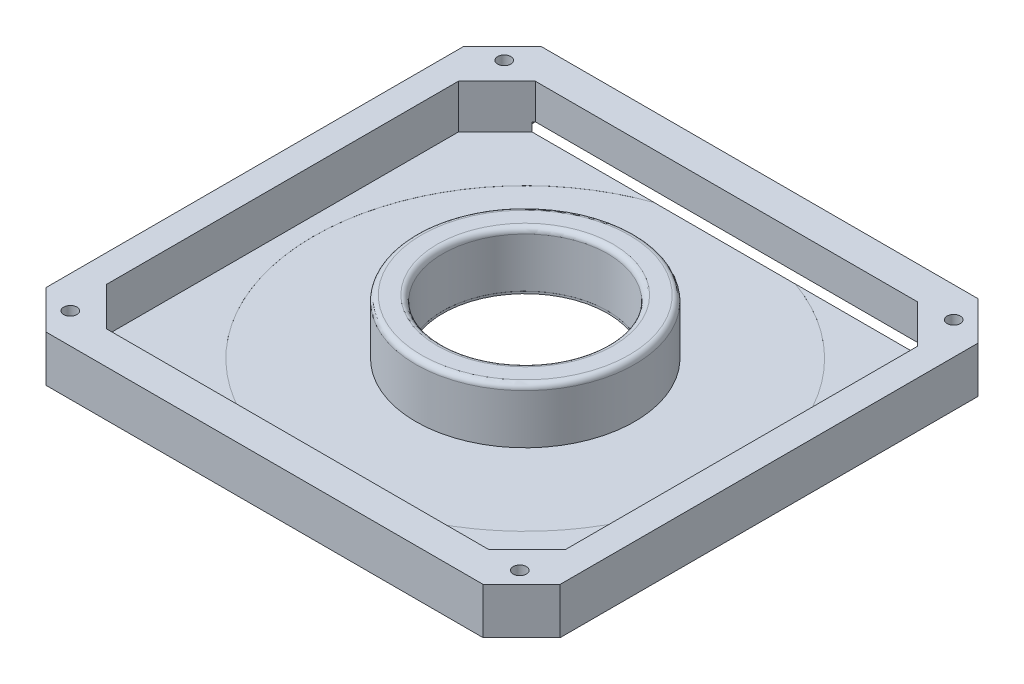
SolidWorks part; units mm, degrees
ref_plane "Front Plane" through (0, 0, 0) normal (0, 0, 1) x (1, 0, 0)
ref_plane "Top Plane" through (0, 0, 0) normal (0, 1, 0) x (1, 0, 0)
ref_plane "Right Plane" through (0, 0, 0) normal (1, 0, 0) x (0, 0, -1)
sketch "Sketch1" plane through (0, 0, 0) normal (0, 1, 0) x (1, 0, 0)
  line L0 (-49.3, 41.6048) -> (-43.2, 47.7048)
  line L1 (-34, -47.5952) -> (34, -47.5952)
  line L2 (-49.3, -37.9952) -> (-49.3, 41.6048)
  line L3 (-43.2, 47.7048) -> (-35.5, 47.7048)
  line L4 (49.3, -37.9952) -> (49.3, 41.6048)
  line L5 (-49.3, -47.5952) -> (49.2706, 47.5669) construction
  line L6 (-49.3548, 47.6481) -> (49.3, -47.5952) construction
  line L7 (0, 0) -> (0, 47.7048) construction
  line L8 (49.3, 41.6048) -> (43.2, 47.7048)
  line L9 (-46.8, -44.0952) -> (-46.8, -38.9952)
  line L10 (-45.8, -45.0952) -> (-35, -45.0952)
  line L11 (46.8, -44.0952) -> (46.8, -38.9952)
  line L12 (-49.3, -37.9952) -> (-47.8, -37.9952)
  line L13 (-34, -47.5952) -> (-34, -46.0952)
  line L14 (34, -47.5952) -> (34, -46.0952)
  line L15 (49.3, -37.9952) -> (47.8, -37.9952)
  line L16 (35, -45.0952) -> (45.8, -45.0952)
  line L17 (-46.8, -45.0952) -> (-46.8, 41.6048) construction
  line L18 (46.8, -45.0952) -> (46.8, 41.6048) construction
  line L19 (-34.5, 44.0048) -> (-4.5, 44.0048)
  line L20 (-46.8, -45.0952) -> (46.8, -45.0952) construction
  line L21 (-49.3, -47.5952) -> (49.3, -47.5952) construction
  line L22 (-49.3, -47.5952) -> (-49.3, 41.6048) construction
  line L23 (49.3, -47.5952) -> (49.3, 41.6048) construction
  line L24 (-35.5, 47.7048) -> (-35.5, 45.0048)
  line L25 (-3.5, 47.7048) -> (-3.5, 45.0048)
  line L26 (-3.5, 47.7048) -> (43.2, 47.7048)
  line L27 (-43.2, 44.0048) -> (43.2, 44.0048) construction
  line L28 (21.27, 40.7348) -> (23.81, 40.7348) construction
  line L29 (-43.2, 47.7048) -> (43.2, 47.7048) construction
  line L30 (28.67, 40.7348) -> (31.21, 40.7348) construction
  line L31 (28.67, 40.7348) -> (28.67, 43.2748) construction
  line L32 (28.67, 43.2748) -> (31.21, 43.2748) construction
  line L33 (31.21, 40.7348) -> (31.21, 43.2748) construction
  line L34 (28.67, 40.7348) -> (31.21, 43.2748) construction
  line L35 (28.67, 43.2748) -> (31.21, 40.7348) construction
  line L36 (21.27, 40.7348) -> (21.27, 43.2748) construction
  line L37 (21.27, 43.2748) -> (23.81, 43.2748) construction
  line L38 (23.81, 40.7348) -> (23.81, 43.2748) construction
  line L39 (21.27, 40.7348) -> (23.81, 43.2748) construction
  line L40 (21.27, 43.2748) -> (23.81, 40.7348) construction
  line L41 (13.87, 40.7348) -> (16.41, 40.7348) construction
  line L42 (13.87, 40.7348) -> (13.87, 43.2748) construction
  line L43 (13.87, 43.2748) -> (16.41, 43.2748) construction
  line L44 (16.41, 40.7348) -> (16.41, 43.2748) construction
  line L45 (13.87, 40.7348) -> (16.41, 43.2748) construction
  line L46 (13.87, 43.2748) -> (16.41, 40.7348) construction
  arc A0 (47.8, -37.9952) -> (46.8, -38.9952) centre (47.8, -38.9952) ccw
  arc A1 (35, -45.0952) -> (34, -46.0952) centre (35, -46.0952) ccw
  arc A2 (-34, -46.0952) -> (-35, -45.0952) centre (-35, -46.0952) ccw
  arc A3 (-46.8, -38.9952) -> (-47.8, -37.9952) centre (-47.8, -38.9952) ccw
  arc A4 (46.8, -44.0952) -> (45.8, -45.0952) centre (45.8, -44.0952) cw
  arc A5 (-45.8, -45.0952) -> (-46.8, -44.0952) centre (-45.8, -44.0952) cw
  arc A6 (-4.5, 44.0048) -> (-3.5, 45.0048) centre (-4.5, 45.0048) ccw
  arc A7 (-34.5, 44.0048) -> (-35.5, 45.0048) centre (-34.5, 45.0048) cw
  circle A8 centre (-33.77, 39.7448) radius 0.4
  circle A9 centre (-5.22, 39.7448) radius 0.4
  circle A10 centre (29.94, 42.0048) radius 0.2125
  circle A11 centre (28.67, 43.2748) radius 0.2125
  circle A12 centre (31.21, 43.2748) radius 0.2125
  circle A13 centre (31.21, 40.7348) radius 0.2125
  circle A14 centre (28.67, 40.7348) radius 0.2125
  circle A15 centre (22.54, 42.0048) radius 0.2125
  circle A16 centre (21.27, 43.2748) radius 0.2125
  circle A17 centre (23.81, 43.2748) radius 0.2125
  circle A18 centre (23.81, 40.7348) radius 0.2125
  circle A19 centre (21.27, 40.7348) radius 0.2125
  circle A20 centre (15.14, 42.0048) radius 0.2125
  circle A21 centre (13.87, 43.2748) radius 0.2125
  circle A22 centre (16.41, 43.2748) radius 0.2125
  circle A23 centre (16.41, 40.7348) radius 0.2125
  circle A24 centre (13.87, 40.7348) radius 0.2125
  point P0 (0, 0)
  point P26 (46.8, -37.9952)
  point P29 (34, -45.0952)
  point P32 (-34, -45.0952)
  point P35 (-46.8, -37.9952)
  dimension "D9" = 1
  dimension "D10" = 1
  dimension "D11" = 3.7
  dimension "D14" = 1
  dimension "D16" = 0.8
  dimension "D18" = 7.96
  dimension "D19" = 9.43
  dimension "D20" = 28.55
  dimension "D21" = 0.425
  dimension "D22" = 1.27
  dimension "D1" = 47.7048
  dimension "D2" = 98.6
  dimension "D3" = 6.1
  dimension "D4" = 6.1
  dimension "D5" = 95.3
  dimension "D6" = 2.5
  dimension "D7" = 85.7
  dimension "D8" = 15.3
  dimension "D12" = 13.8
  dimension "D13" = 32
  dimension "D15" = 137.1279
  dimension "D17" = 7.96
  dimension "D23" = 5.7
  dimension "D24" = 13.26
  dimension "D25" = 1.27
  dimension "D27" = 5.7
  dimension "D28" = 7.4
  dimension "D26" = 3
sketch "Sketch4" plane through (0, 0, 0) normal (0, 1, 0) x (1, 0, 0)
  line L0 (-46.75, 38) -> (-39.75, 45)
  line L1 (-39.75, -45) -> (39.75, -45)
  line L2 (-46.75, -38) -> (-46.75, 38)
  line L3 (-39.75, 45) -> (39.75, 45)
  line L4 (46.75, -38) -> (46.75, 38)
  line L5 (-46.75, -45) -> (46.75, 45) construction
  line L6 (-46.75, 45) -> (46.75, -45) construction
  line L7 (39.75, 45) -> (46.75, 38)
  line L8 (-39.75, -45) -> (-46.75, -38)
  line L9 (39.75, -45) -> (46.75, -38)
  point P0 (0, 0)
  dimension "D1" = 93.5
  dimension "D2" = 90
extrude "Boss-Extrude1" add sketch "Sketch4" along normal blind 8.4
sketch "Sketch5" plane through (0, 0, 0) normal (0, -1, 0) x (1, 0, 0)
  line L0 (36.75, -45) -> (36.75, -39.7048)
  line L1 (39.75, -45) -> (-39.75, -45) construction
  line L2 (35.75, -38.7048) -> (-35.75, -38.7048)
  line L3 (-36.75, -39.7048) -> (-36.75, -45)
  line L5 (46.75, 38) -> (46.75, -38) construction
  line L7 (-46.75, -38) -> (-46.75, 38) construction
  line L9 (-3.5, -47.7048) -> (43.2, -47.7048) construction
  arc A0 (-36.75, -39.7048) -> (-35.75, -38.7048) centre (-35.75, -39.7048) cw
  arc A1 (35.75, -38.7048) -> (36.75, -39.7048) centre (35.75, -39.7048) cw
  dimension "D4" = 1
  dimension "D1" = 10
  dimension "D2" = 10
  dimension "D3" = 9
extrude "Cut-Extrude1" cut sketch "Sketch5" against normal blind 2 and the other way through all
sketch "Sketch6" plane through (0, 8.4, 0) normal (0, 1, 0) x (1, 0, 0)
  line L0 (-41.75, 32) -> (-34.75, 39)
  line L1 (-34.75, -39) -> (34.75, -39)
  line L2 (-41.75, -32) -> (-41.75, 32)
  line L3 (-34.75, 39) -> (34.75, 39)
  line L4 (41.75, -32) -> (41.75, 32)
  line L5 (-41.75, -39) -> (41.75, 39) construction
  line L6 (-41.75, 39) -> (41.75, -39) construction
  line L7 (34.75, 39) -> (41.75, 32)
  line L8 (34.75, -39) -> (41.75, -32)
  line L9 (-41.75, -32) -> (-34.75, -39)
  point P0 (0, 0)
  dimension "D1" = 78
  dimension "D2" = 83.5
extrude "Cut-Extrude2" cut sketch "Sketch6" against normal blind 8
sketch "Sketch8" plane through (0, 0.4, 0) normal (0, 1, 0) x (1, 0, 0)
  line L1 (34.75, 39) -> (-34.75, 39) construction
  line L2 (-41.75, 32) -> (-41.75, -32) construction
  circle A0 centre (0, 2.4048) radius 38.5 construction
  circle A1 centre (0, 2.4048) radius 19.9
  dimension "D1" = 77
  dimension "D2" = 39.8
  dimension "D3" = 36.5952
  dimension "D4" = 41.75
extrude "Boss-Extrude2" add sketch "Sketch8" along normal blind 10
fillet "Fillet1" radius 1 1 edges at (0, 10.4, 17.4952)
sketch "Sketch9" plane through (0, 0.4, 0) normal (0, 1, 0) x (1, 0, 0)
  circle A0 centre (0, 2.4048) radius 38.5
  dimension "D1" = 77
extrude "Cut-Extrude4" cut sketch "Sketch9" against normal blind 0.01
hole_wizard "M2 Clearance Hole1" positions "Sketch12" profile "Sketch10" hole size "M2" standard "ANSI Metric"
sketch "Sketch12" plane through (0, 8.4, 0) normal (0, 1, 0) x (1, 0, 0)
  line L0 (-49.3548, 47.6481) -> (49.3, -47.5952) construction
  line L1 (-49.3, -47.5952) -> (49.2706, 47.5669) construction
  point P0 (40.8712, -39.4579)
  point P4 (-40.8712, -39.4579)
  point P8 (-40.8712, 39.4579)
  point P10 (40.8712, 39.4579)
  dimension "D1" = 56.81
  dimension "D2" = 56.81
  dimension "D3" = 56.81
  dimension "D4" = 56.81
sketch "Sketch10" plane through (40.8712, 8.4, 39.4579) normal (1, 0, 0) x (0, 0, 1)
  line L0 (0, 0) -> (0, 38.821)
  line L1 (0, 38.821) -> (1.2, 38.1)
  line L2 (1.2, 38.1) -> (1.2, 0)
  line L5 (1.2, 0) -> (0, 0)
  line L10 (0, 38.821) -> (-1.2, 38.1) construction
  line L11 (0, -6.35) -> (0, 107.95) construction
  dimension "Hole Dia." = 2.4
  dimension "Hole Depth" = 38.1
  dimension "Drill Angle" = 118
sketch "Sketch13" plane through (0, 10.4, 0) normal (0, 1, 0) x (1, 0, 0)
  circle A0 centre (0, 2.4048) radius 15
  circle A1 centre (0, 2.4048) radius 18.9 construction
  dimension "D1" = 30
extrude "Cut-Extrude5" cut sketch "Sketch13" against normal through all
fillet "Fillet2" radius 1 1 edges at (0, 10.4, 12.5952)
